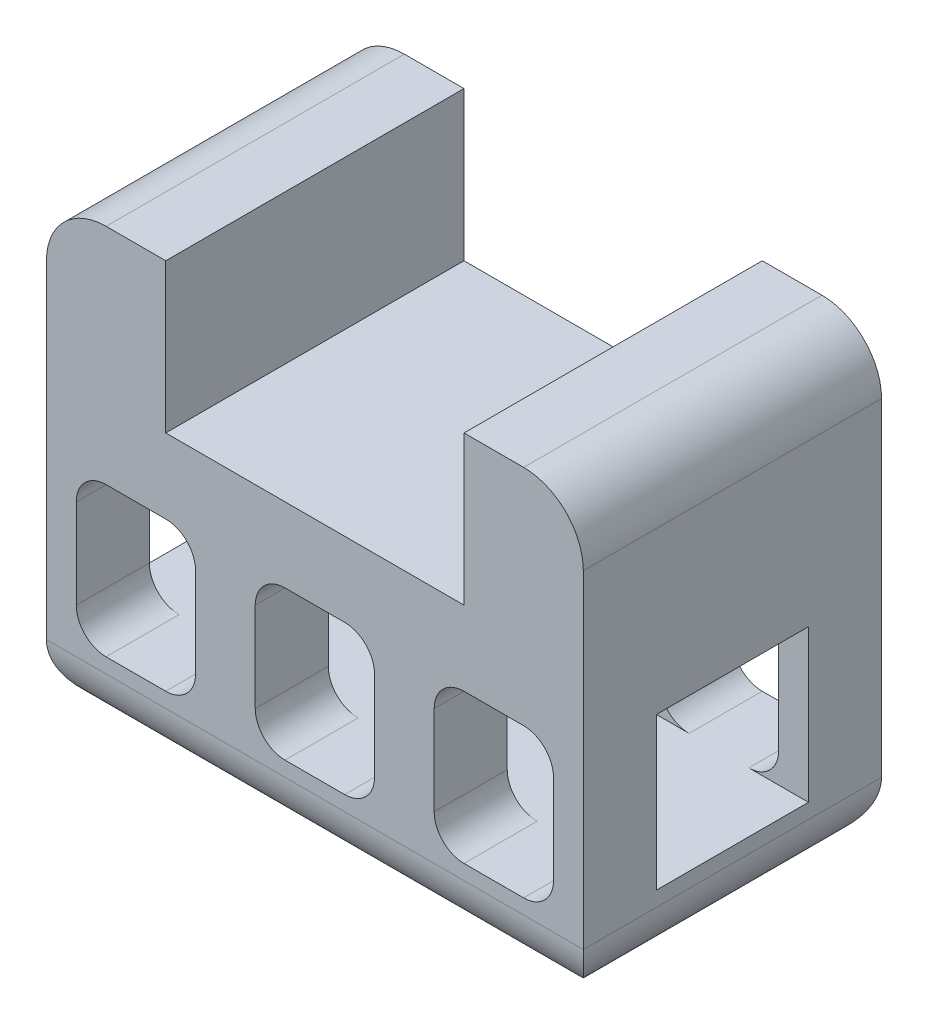
SolidWorks part; units mm, degrees
ref_plane "Front Plane" through (0, 0, 0) normal (0, 0, 1) x (1, 0, 0)
ref_plane "Top Plane" through (0, 0, 0) normal (0, 1, 0) x (1, 0, 0)
ref_plane "Right Plane" through (0, 0, 0) normal (1, 0, 0) x (0, 0, -1)
sketch "Sketch1" plane through (0, 0, 0) normal (0, 0, 1) x (1, 0, 0)
  line L5 (-10, 15) -> (-10, 5)
  line L6 (-18, 15) -> (-10, 15)
  line L9 (-18, 15) -> (-18, -15)
  line L15 (-18, -15) -> (18, -15)
  line L16 (18, 15) -> (18, -15)
  line L17 (-18, 15) -> (18, -15) construction
  line L18 (-18, -15) -> (18, 15) construction
  line L19 (10, 5) -> (-10, 5)
  line L20 (10, 15) -> (10, 5)
  line L21 (10, 15) -> (18, 15)
  line L22 (0, 38.6137) -> (0, 0) construction
  point P0 (0, 0)
  dimension "D1" = 20
  dimension "D2" = 30
  dimension "12" = 8
  dimension "10" = 10
extrude "Boss-Extrude1" add sketch "Sketch1" along normal blind 20
sketch "Sketch5" plane through (-18, 0, 0) normal (-1, 0, 0) x (0, 0, 1)
  line L0 (10, 15) -> (10, -15) construction
  line L1 (20, 15) -> (0, 15) construction
  line L2 (20, -15) -> (0, -15) construction
  line L4 (4.9, 0.2) -> (15.1, 0.2)
  line L5 (4.9, 0.2) -> (4.9, -10)
  line L6 (4.9, -10) -> (15.1, -10)
  line L7 (15.1, 0.2) -> (15.1, -10)
  line L8 (4.9, 0.2) -> (15.1, -10) construction
  line L9 (4.9, -10) -> (15.1, 0.2) construction
  point P6 (10, -4.9)
  dimension "D1" = 10.2
  dimension "D2" = 10.2
  dimension "D3" = 5
extrude "Cut-Extrude2" cut sketch "Sketch5" against normal through all
sketch "Sketch6" plane through (0, 0, 20) normal (0, 0, 1) x (1, 0, 0)
  line L0 (-23.3455, -10) -> (16, -10) construction
  line L1 (-18, -15) -> (18, -15) construction
  line L2 (-4, -10) -> (4, -10)
  line L3 (-16, -10) -> (-8, -10)
  line L4 (-16, -10) -> (-16, 0)
  line L5 (-16, 0) -> (-8, 0)
  line L6 (-8, -10) -> (-8, 0)
  line L7 (-4, -10) -> (-4, 0)
  line L8 (-4, 0) -> (4, 0)
  line L9 (4, -10) -> (4, 0)
  line L10 (8, -10) -> (16, -10)
  line L11 (8, -10) -> (8, 0)
  line L12 (8, 0) -> (16, 0)
  line L13 (16, -10) -> (16, 0)
  line L14 (-18, 15) -> (-18, -15) construction
  line L15 (18, 15) -> (18, -15) construction
  line L16 (0, 0) -> (0, -16.6181) construction
  dimension "D1" = 10
  dimension "D2" = 8
  dimension "D3" = 5
  dimension "D4" = 2
  dimension "D5" = 2
extrude "Cut-Extrude3" cut sketch "Sketch6" against normal through all
fillet "Fillet1" radius 2 24 edges at (-16, -10, 17.55) (8, -10, 2.45) (-4, -10, 2.45) (-16, -10, 2.45) (4, -10, 2.45) (-8, -10, 2.45) (16, -10, 2.45) (16, -10, 17.55) (8, -10, 17.55) (4, -10, 17.55) (-4, -10, 17.55) (-8, -10, 17.55) (8, 0, 17.55) (16, 0, 17.55) (16, 0, 2.45) (8, 0, 2.45) (-8, 0, 2.45) (-8, 0, 17.55) (4, 0, 2.45) (4, 0, 17.55) (-4, 0, 17.55) (-4, 0, 2.45) (-16, 0, 2.45) (-16, 0, 17.55)
fillet "Fillet3" radius 4 4 edges at (-18, -15, 10) (0, -15, 20) (18, -15, 10) (0, -15, 0)
fillet "Fillet4" radius 4 2 edges at (-18, 15, 10) (18, 15, 10)
